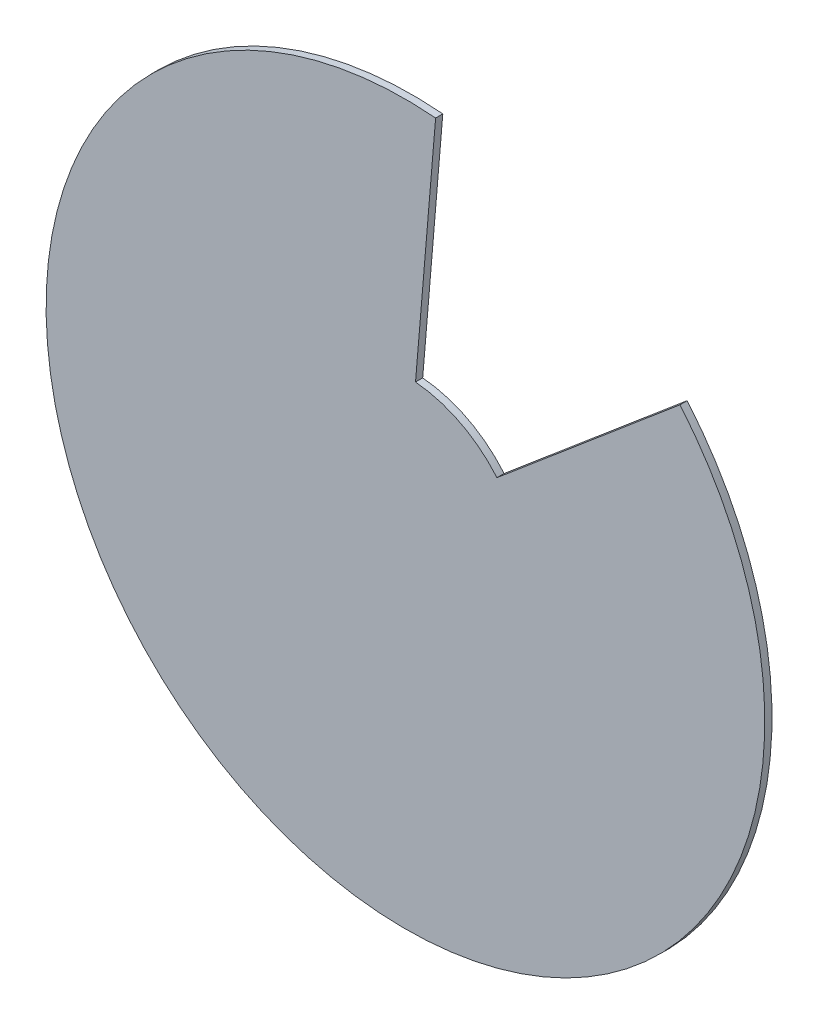
SolidWorks part; units mm, degrees
ref_plane "Front Plane" through (0, 0, 0) normal (0, 0, 1) x (1, 0, 0)
ref_plane "Top Plane" through (0, 0, 0) normal (0, 1, 0) x (1, 0, 0)
ref_plane "Right Plane" through (0, 0, 0) normal (1, 0, 0) x (0, 0, -1)
sketch "Sketch1" plane through (0, 0, 0) normal (0, 0, 1) x (1, 0, 0)
  line L0 (4.1973, 49.8235) -> (12.5919, 149.4705)
  line L1 (38.1985, 32.2626) -> (114.5955, 96.7878)
  arc A0 (12.5919, 149.4705) -> (114.5955, 96.7878) centre (0, 0) ccw
  arc A1 (38.1985, 32.2626) -> (4.1973, 49.8235) centre (0, 0) ccw
  point P1 (0, 0)
  dimension "D1" = 45
  dimension "D2" = 150
  dimension "D3" = 50
extrude "Boss-Extrude1" add sketch "Sketch1" along normal blind 3
